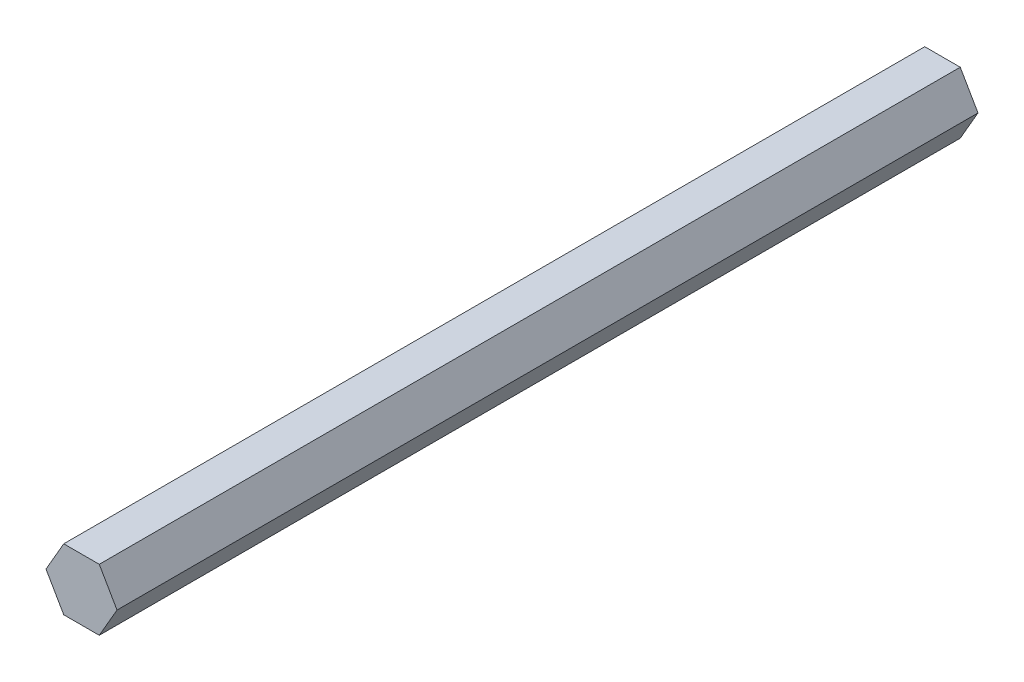
SolidWorks part; units mm, degrees
ref_plane "Front Plane" through (0, 0, 0) normal (0, 0, 1) x (1, 0, 0)
ref_plane "Top Plane" through (0, 0, 0) normal (0, 1, 0) x (1, 0, 0)
ref_plane "Right Plane" through (0, 0, 0) normal (1, 0, 0) x (0, 0, -1)
sketch "Sketch1" plane through (0, 0, 0) normal (0, 0, 1) x (1, 0, 0)
  line L0 (3.6662, 6.35) -> (-3.6662, 6.35)
  line L1 (-3.6662, 6.35) -> (-7.3323, 0)
  line L2 (-7.3323, 0) -> (-3.6662, -6.35)
  line L3 (-3.6662, -6.35) -> (3.6662, -6.35)
  line L4 (3.6662, -6.35) -> (7.3323, 0)
  line L5 (7.3323, 0) -> (3.6662, 6.35)
  circle A0 centre (0, 0) radius 6.35 construction
  dimension "D1" = 12.7
extrude "Boss-Extrude1" add sketch "Sketch1" along normal mid plane 177.8
